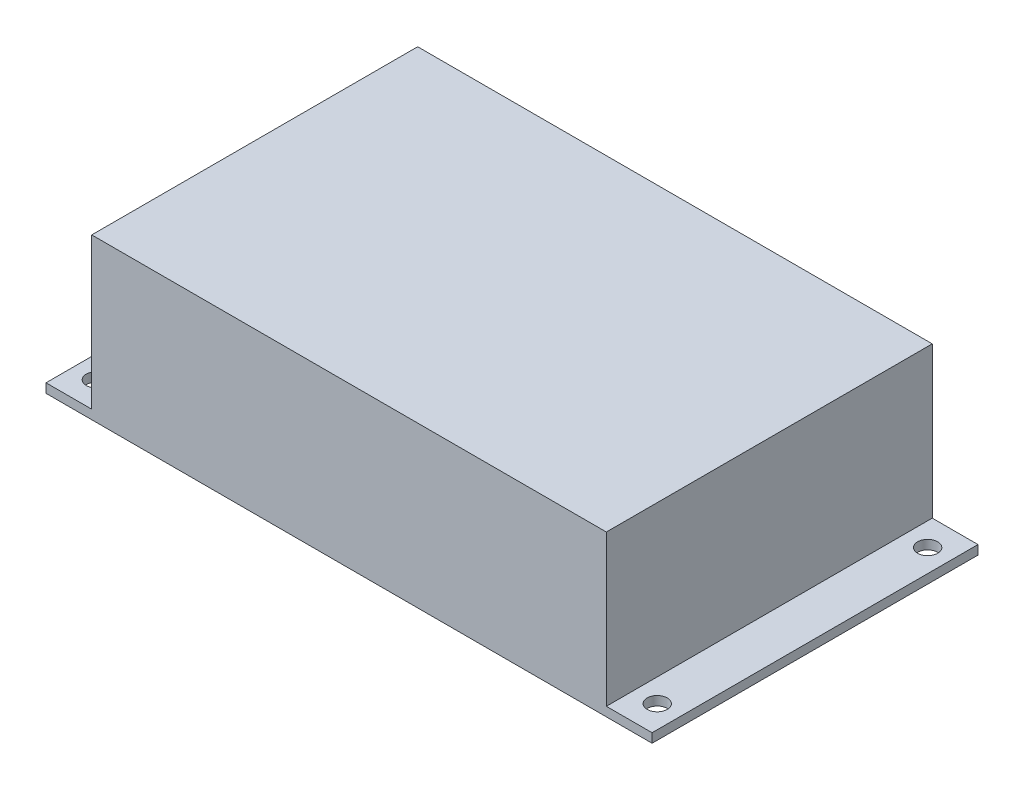
SolidWorks part; units mm, degrees
ref_plane "前视" through (0, 0, 0) normal (0, 0, 1) x (1, 0, 0)
ref_plane "上视" through (0, 0, 0) normal (0, 1, 0) x (1, 0, 0)
ref_plane "右视" through (0, 0, 0) normal (1, 0, 0) x (0, 0, -1)
sketch "草图1" plane through (0, 0, 0) normal (0, 1, 0) x (1, 0, 0)
  line L0 (-106.8768, 0) -> (85.3196, 0) construction
  line L1 (-53, 28.5) -> (53, 28.5)
  line L2 (-53, 28.5) -> (-53, -28.5)
  line L3 (-53, -28.5) -> (53, -28.5)
  line L4 (53, 28.5) -> (53, -28.5)
  line L5 (0, 69.3465) -> (0, -69.6063) construction
  dimension "D1" = 106
  dimension "D2" = 57
extrude "凸台-拉伸1" add sketch "草图1" along normal blind 1.6
sketch "草图2" plane through (0, 1.6, 0) normal (0, 1, 0) x (1, 0, 0)
  line L0 (-49.3624, 0) -> (61.9395, 0) construction
  line L1 (0, 27.7214) -> (0, -30.4894) construction
  circle A0 centre (-49.05, 23.65) radius 1.75
  circle A1 centre (-49.05, -23.65) radius 1.75
  circle A2 centre (49.05, -23.65) radius 1.75
  circle A3 centre (49.05, 23.65) radius 1.75
  dimension "D3" = 3.5
  dimension "D1" = 98.1
  dimension "D2" = 47.3
extrude "切除-拉伸1" cut sketch "草图2" against normal blind 1.6
sketch "草图3" plane through (0, 1.6, 0) normal (0, 1, 0) x (1, 0, 0)
  line L0 (53, 28.5) -> (-53, 28.5) construction
  line L1 (-45, 28.5) -> (45, 28.5)
  line L2 (-45, 28.5) -> (-45, -28.5)
  line L3 (-45, -28.5) -> (45, -28.5)
  line L4 (45, 28.5) -> (45, -28.5)
  line L5 (-53, -28.5) -> (53, -28.5) construction
  line L6 (0, 46.5122) -> (0, -44.0401) construction
  line L7 (-53, 28.5) -> (-53, -28.5) construction
  dimension "D1" = 8
extrude "凸台-拉伸2" add sketch "草图3" along normal offset from surface (26.4 mm away) 28 up to face at (49.05, 0, -25.4)
